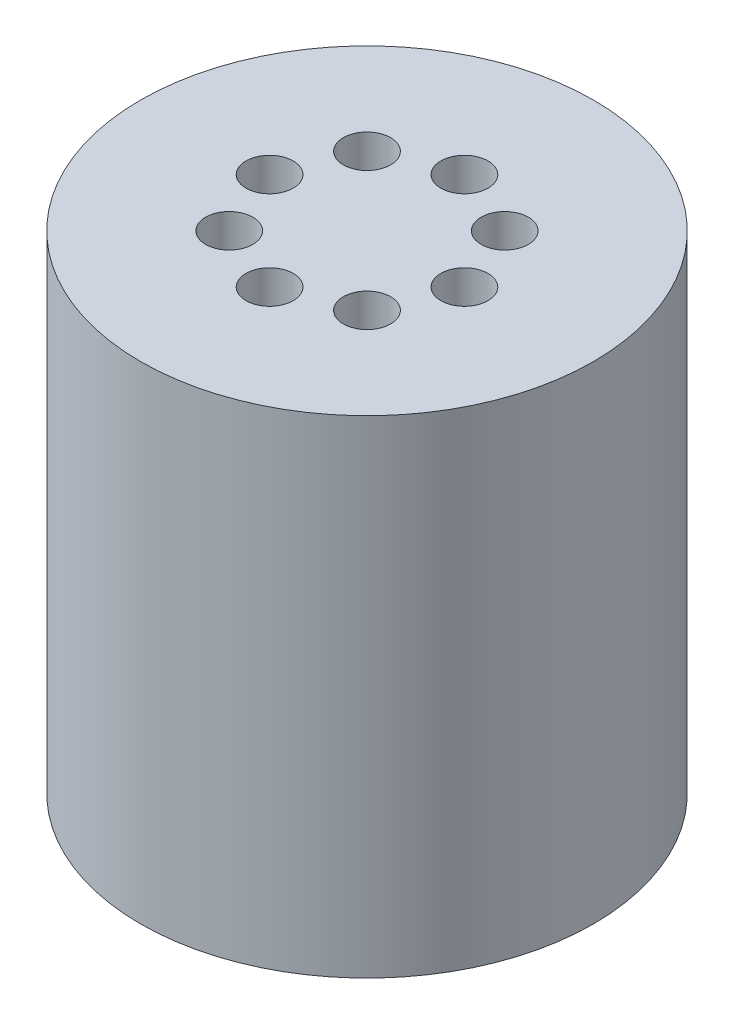
SolidWorks part; units mm, degrees
material "6061 Alloy"
ref_plane "Front Plane" through (0, 0, 0) normal (0, 0, 1) x (1, 0, 0)
ref_plane "Top Plane" through (0, 0, 0) normal (0, 1, 0) x (1, 0, 0)
ref_plane "Right Plane" through (0, 0, 0) normal (1, 0, 0) x (0, 0, -1)
sketch "Sketch1" plane through (0, 0, 0) normal (0, 1, 0) x (1, 0, 0)
  circle A0 centre (0, 0) radius 23.25
  dimension "D1" = 46.5
extrude "Boss-Extrude1" add sketch "Sketch1" along normal blind 50
sketch "Sketch2" plane through (0, 50, 0) normal (0, 1, 0) x (1, 0, 0)
  circle A0 centre (0, 0) radius 10
  circle A1 centre (0, 10) radius 2.425
  circle A2 centre (7.0711, 7.0711) radius 2.425
  circle A3 centre (10, 0) radius 2.425
  circle A4 centre (7.0711, -7.0711) radius 2.425
  circle A5 centre (0, -10) radius 2.425
  circle A6 centre (-7.0711, -7.0711) radius 2.425
  circle A7 centre (-10, 0) radius 2.425
  circle A8 centre (-7.0711, 7.0711) radius 2.425
  dimension "D1" = 20
  dimension "D2" = 4.85
  dimension "D3" = 8
extrude "Cut-Extrude1" cut sketch "Sketch2" against normal blind 5 contours A1 | A8 | A6 | A7 | A5 | A4 | A3 | A2
